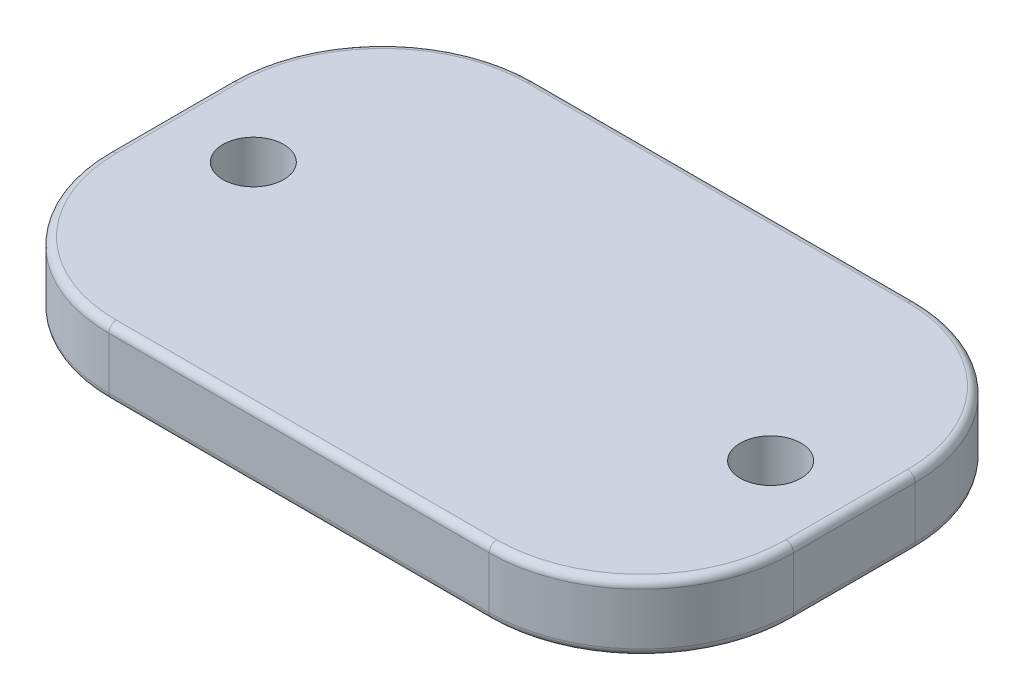
SolidWorks part; units mm, degrees
ref_plane "Front Plane" through (0, 0, 0) normal (0, 0, 1) x (1, 0, 0)
ref_plane "Top Plane" through (0, 0, 0) normal (0, 1, 0) x (1, 0, 0)
ref_plane "Right Plane" through (0, 0, 0) normal (1, 0, 0) x (0, 0, -1)
sketch "Sketch1" plane through (0, 0, 0) normal (0, 1, 0) x (1, 0, 0)
  line L1 (-22.5, -14) -> (22.5, -14)
  line L2 (-22.5, -14) -> (-22.5, 14)
  line L3 (-22.5, 14) -> (22.5, 14)
  line L4 (22.5, -14) -> (22.5, 14)
  line L5 (-22.5, -14) -> (22.5, 14) construction
  line L6 (-22.5, 14) -> (22.5, -14) construction
  point P0 (0, 0)
  dimension "D1" = 28
  dimension "D2" = 45
extrude "Boss-Extrude1" add sketch "Sketch1" along normal blind 4.4
sketch "Sketch2" plane through (0, 4.4, 0) normal (0, 1, 0) x (1, 0, 0)
  line L0 (-17, 0) -> (17, 0) construction
  circle A0 centre (-17, 0) radius 2
  circle A1 centre (17, 0) radius 2
  point P4 (0, 0)
  dimension "D2" = 4
  dimension "D3" = 4
  dimension "D1" = 34
extrude "Cut-Extrude1" cut sketch "Sketch2" against normal blind 4.4
fillet "Fillet1" radius 10 4 edges at (22.5, 2.2, 14) (22.5, 2.2, -14) (-22.5, 2.2, -14) (-22.5, 2.2, 14)
sketch "Sketch4" plane through (0, 0, 0) normal (0, 0, 1) x (1, 0, 0)
  line L0 (0, 0) -> (0, 2) construction
  line L1 (-10.5, 2) -> (10.5, 2) construction
  line L2 (-12.5, 0) -> (12.5, 0) construction
  line L3 (0, 2) -> (0, -8.5)
  line L4 (0, 2) -> (10.5, 2)
  arc A0 (-10.5, 2) -> (10.5, 2) centre (0, 2) ccw construction
  arc A1 (0, -8.5) -> (10.5, 2) centre (0, 2) ccw
  point P3 (-10.3078, 0)
  point P6 (10.3078, 0)
  dimension "D1" = 21
  dimension "D2" = 2
revolve "Revolve1" add sketch "Sketch4" angle 360 about L3
sketch "Sketch5" plane through (0, 0, 0) normal (0, 0, 1) x (1, 0, 0)
  line L0 (-12.5, 4.4) -> (12.5, 4.4) construction
  line L1 (-6.6813, -10.9) -> (6.6813, -10.9)
  line L2 (-6.6813, -10.9) -> (-6.6813, -6.1)
  line L3 (-6.6813, -6.1) -> (6.6813, -6.1)
  line L4 (6.6813, -10.9) -> (6.6813, -6.1)
  line L5 (-6.6813, -10.9) -> (6.6813, -6.1) construction
  line L6 (-6.6813, -6.1) -> (6.6813, -10.9) construction
  arc A1 (-10.3078, 0) -> (10.3078, 0) centre (0, 2) ccw construction
  point P0 (0, -8.5)
  dimension "D1" = 10.5
extrude "Cut-Extrude2" cut sketch "Sketch5" against normal mid plane 24.4
fillet "Fillet2" radius 0.5 16 edges at (0, 0, 14) (19.5711, 0, 11.0711) (22.5, 0, 0) (19.5711, 0, -11.0711) (0, 0, -14) (-19.5711, 0, -11.0711) (-22.5, 0, 0) (-22.5, 4.4, 0) (-19.5711, 4.4, -11.0711) (0, 4.4, -14) (19.5711, 4.4, -11.0711) (22.5, 4.4, 0) (19.5711, 4.4, 11.0711) (0, 4.4, 14) (-19.5711, 0, 11.0711) (-19.5711, 4.4, 11.0711)
ref_plane "Plane1" through (0, -3.1, 0) normal (0, -1, 0) x (-1, 0, 0)
sketch "Sketch6" plane through (0, -3.1, 0) normal (0, -1, 0) x (-1, 0, 0)
  line L0 (0, -6) -> (0, 6)
  arc A0 (0, -6) -> (0, 6) centre (0, 0) ccw
  point P4 (0, 0)
  dimension "D1" = 6
revolve "Revolve2" add sketch "Sketch6" angle 360 about L0
